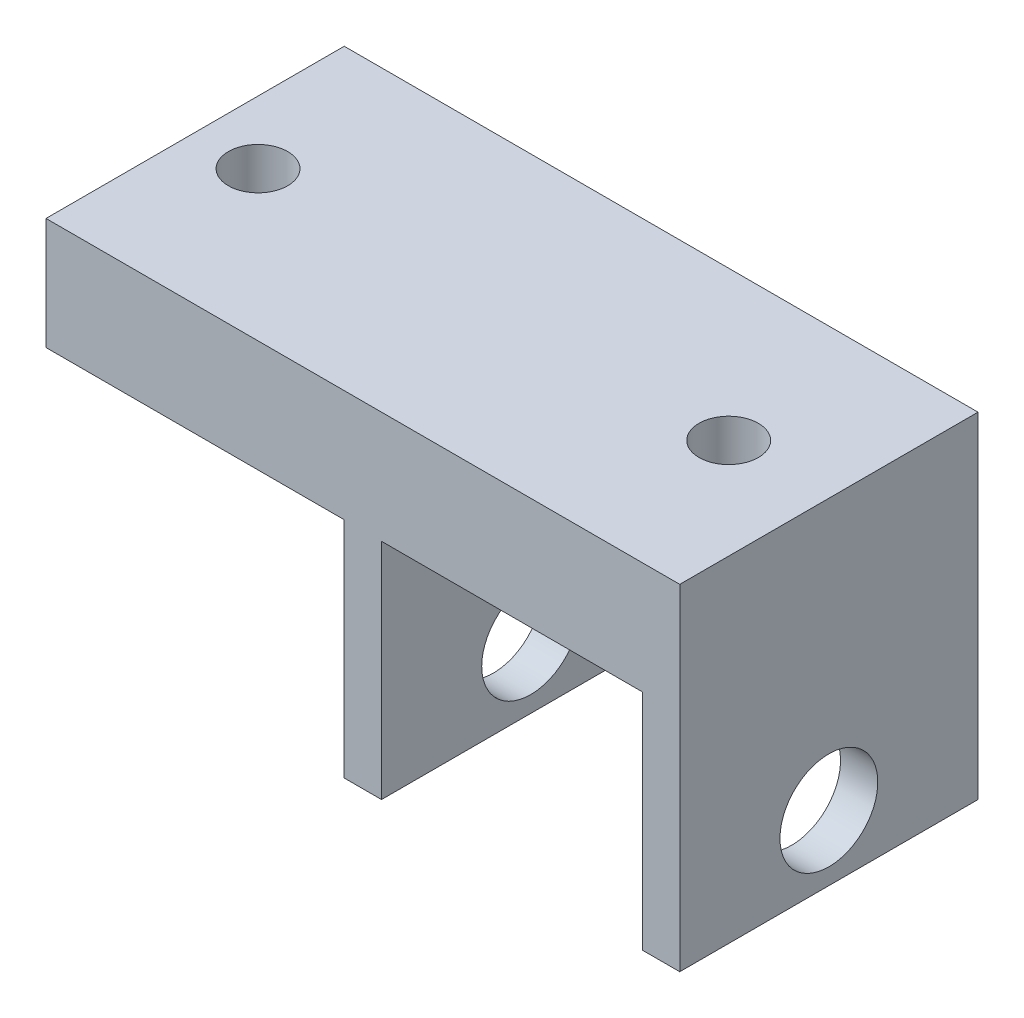
SolidWorks part; units mm, degrees
ref_plane "Front Plane" through (0, 0, 0) normal (0, 0, 1) x (1, 0, 0)
ref_plane "Top Plane" through (0, 0, 0) normal (0, 1, 0) x (1, 0, 0)
ref_plane "Right Plane" through (0, 0, 0) normal (1, 0, 0) x (0, 0, -1)
sketch "Sketch1" plane through (0, 0, 0) normal (0, 0, 1) x (1, 0, 0)
  line L0 (-14.2875, 9.525) -> (-14.2875, -9.525)
  line L1 (-39.6875, 19.05) -> (14.2875, 19.05)
  line L2 (-39.6875, 19.05) -> (-39.6875, 9.525)
  line L3 (-39.6875, 9.525) -> (-14.2875, 9.525)
  line L4 (14.2875, 19.05) -> (14.2875, -9.525)
  line L5 (-14.2875, -9.525) -> (-11.1125, -9.525)
  line L6 (-11.1125, -9.525) -> (-11.1125, 9.525)
  line L7 (11.1125, -9.525) -> (14.2875, -9.525)
  line L8 (11.1125, -9.525) -> (11.1125, 9.525)
  line L9 (11.1125, 9.525) -> (-11.1125, 9.525)
  point P1 (0, 9.525)
  point P11 (-11.1125, 0)
  dimension "D1" = 22.225
  dimension "D2" = 3.175
  dimension "D3" = 3.175
  dimension "D4" = 9.525
  dimension "D5" = 19.05
  dimension "D6" = 53.975
extrude "Boss-Extrude1" add sketch "Sketch1" along normal blind 25.4 contours L1 L4 L7 L8 L9 L6 L5 L0 L3 L2
sketch "Sketch2" plane through (-14.2875, 0, 0) normal (-1, 0, 0) x (0, 0, 1)
  line L0 (12.7, -9.525) -> (12.7, 9.525) construction
  line L1 (25.4, -9.525) -> (0, -9.525) construction
  line L2 (25.4, 9.525) -> (0, 9.525) construction
  circle A0 centre (12.7, -3.9687) radius 4.1672
  dimension "D1" = 8.3344
  dimension "D2" = 5.5562
extrude "Cut-Extrude1" cut sketch "Sketch2" against normal through all
sketch "Sketch3" plane through (0, 19.05, 0) normal (0, 1, 0) x (1, 0, 0)
  line L0 (-12.7, 0) -> (-12.7, -25.4) construction
  line L1 (-39.6875, 0) -> (14.2875, 0) construction
  line L2 (-39.6875, -25.4) -> (14.2875, -25.4) construction
  point P0 (-34.3297, -12.7)
  point P1 (5.7547, -12.7)
  point P9 (-12.7, -12.7)
  dimension "D1" = 40.0844
  dimension "D2" = 21.6297
hole_wizard "#8 (0.199) Diameter Hole1" positions "Sketch4" profile "Sketch5" hole size "#8" standard "ANSI Inch" end condition through all
sketch "Sketch4" plane through (0, 19.05, 0) normal (0, 1, 0) x (1, 0, 0)
  point P0 (-34.3297, -12.7)
  point P3 (5.7547, -12.7)
sketch "Sketch5" plane through (-34.3297, 19.05, 12.7) normal (1, 0, 0) x (0, 0, 1)
  line L0 (0, 0) -> (0, 28.575)
  line L1 (0, 28.575) -> (2.5273, 28.575)
  line L2 (2.5273, 28.575) -> (2.5273, 0)
  line L5 (2.5273, 0) -> (0, 0)
  line L11 (0, -6.35) -> (0, 107.95) construction
  dimension "Thru Hole Dia." = 5.0546
  dimension "Thru Hole Depth" = 28.575
